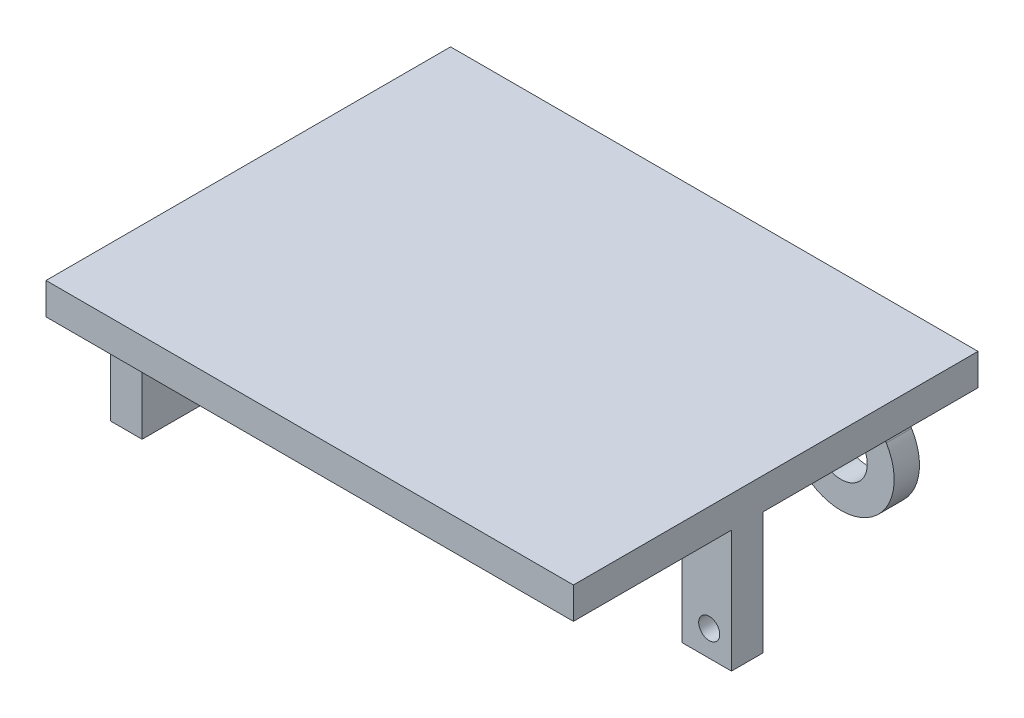
SolidWorks part; units mm, degrees
ref_plane "Plan de face" through (0, 0, 0) normal (0, 0, 1) x (1, 0, 0)
ref_plane "Plan de dessus" through (0, 0, 0) normal (0, 1, 0) x (1, 0, 0)
ref_plane "Plan de droite" through (0, 0, 0) normal (1, 0, 0) x (0, 0, -1)
sketch "Esquisse1" plane through (0, 0, 0) normal (0, 0, 1) x (1, 0, 0)
  line L0 (-39.4472, 12.1289) -> (10.6098, 12.1289)
  line L1 (-39.4472, 9.1329) -> (-13.4707, 9.1329)
  line L4 (10.6098, 9.1329) -> (10.6098, 12.1289)
  line L7 (-39.4472, 12.1289) -> (-39.4472, 9.1329)
  line L8 (0.3756, 9.1329) -> (10.6098, 9.1329)
  line L51 (4.3043, 2.6499) -> (0.3756, 9.1329)
  line L64 (-13.4707, 9.1329) -> (-3.358, -3.7779)
  circle A0 centre (0, 0) radius 2.5
  arc A1 (-3.358, -3.7779) -> (4.3043, 2.6499) centre (0, 0) ccw
extrude "Boss.-Extru.1" add sketch "Esquisse1" along normal blind 2.4
sketch "Esquisse4" plane through (0, 0, 2.4) normal (0, 0, 1) x (1, 0, 0)
  line L0 (-39.4472, 9.1329) -> (-13.4707, 9.1329) construction
  line L1 (-39.4472, 12.1289) -> (-39.4472, 9.1329) construction
  line L2 (10.6098, 9.1329) -> (10.6098, 12.1289) construction
  line L3 (10.6098, 12.1289) -> (-39.4472, 12.1289) construction
  line L4 (-39.4472, 9.1329) -> (10.6098, 9.1329)
  line L5 (-39.4472, 12.1289) -> (-39.4472, 9.1329)
  line L6 (10.6098, 9.1329) -> (10.6098, 12.1289)
  line L7 (10.6098, 12.1289) -> (-39.4472, 12.1289)
extrude "Boss.-Extru.2" add sketch "Esquisse4" along normal blind 36
sketch "Esquisse5" plane through (0, 0, 38.4) normal (0, 0, 1) x (1, 0, 0)
  line L1 (5.9098, 9.1329) -> (10.6098, 9.1329)
  line L2 (5.9098, 9.1329) -> (5.9098, -2.4571)
  line L3 (5.9098, -2.4571) -> (10.6098, -2.4571)
  line L4 (10.6098, 9.1329) -> (10.6098, -2.4571)
  line L5 (-24.6902, 9.1329) -> (-17.6902, 9.1329)
  line L6 (-24.6902, 9.1329) -> (-24.6902, -2.4601)
  line L7 (-24.6902, -2.4601) -> (-17.6902, -2.4601)
  line L8 (-17.6902, 9.1329) -> (-17.6902, -2.4601)
  circle A0 centre (8.5, 0) radius 1
  circle A1 centre (-19.5, 0) radius 1
  point P5 (5.9098, 3.3379)
  dimension "D3" = 4.7
  dimension "D5" = 7
  dimension "D6" = 11.593
  dimension "D10" = 11.59
extrude "Boss.-Extru.3" add sketch "Esquisse5" against normal blind 3 from offset 15 offset against normal yes
sketch "Esquisse6" plane through (-39.4472, 0, -39.4472) normal (1, 0, 0) x (0, 0, -1)
  line L0 (-45.5713, -2.4911) -> (-45.5713, 9.1329)
  line L1 (-71.7232, -2.4911) -> (-71.7232, 9.1329)
  line L2 (-71.7232, 9.1329) -> (-45.5713, 9.1329) construction
  line L3 (-64.7713, -2.4911) -> (-64.7713, 9.1329)
  line L4 (-71.7232, 9.1329) -> (-64.7713, 9.1329)
  line L5 (-71.7232, -2.4911) -> (-64.7713, -2.4911)
  line L6 (-52.5232, -2.4911) -> (-52.5232, 9.1329)
  line L7 (-52.5232, -2.4911) -> (-45.5713, -2.4911)
  line L8 (-45.5713, 9.1329) -> (-52.5232, 9.1329)
  line L9 (-77.8472, 9.1329) -> (-39.4472, 9.1329) construction
  point P8 (-58.6472, 9.1329)
  point P9 (-58.6472, 9.1329)
  dimension "D2" = 6.952
  dimension "D3" = 12.248
  dimension "D4" = 6.952
  dimension "D5" = 11.624
extrude "Boss.-Extru.4" add sketch "Esquisse6" along normal blind 3
